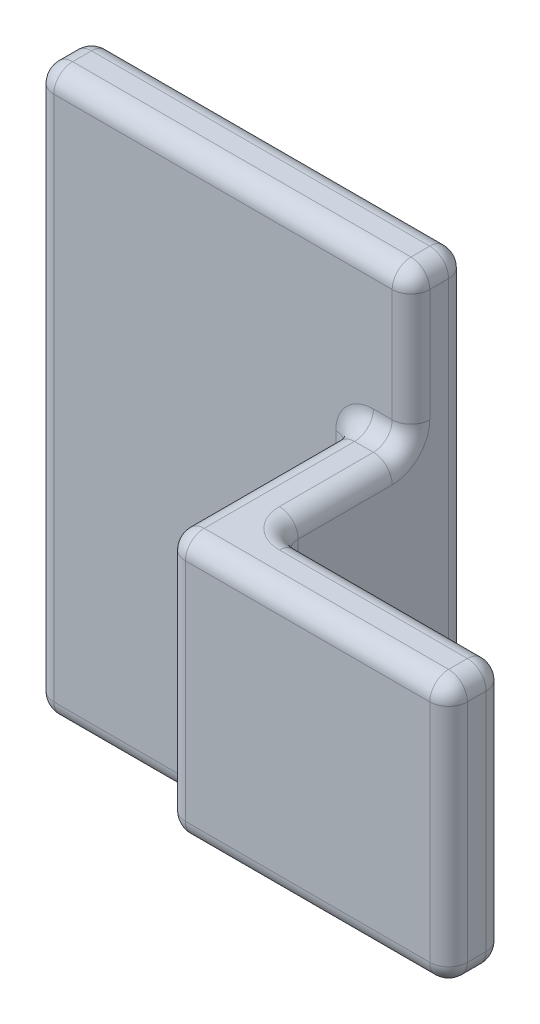
SolidWorks part; units mm, degrees
ref_plane "Front Plane" through (0, 0, 0) normal (0, 0, 1) x (1, 0, 0)
ref_plane "Top Plane" through (0, 0, 0) normal (0, 1, 0) x (1, 0, 0)
ref_plane "Right Plane" through (0, 0, 0) normal (1, 0, 0) x (0, 0, -1)
sketch "Sketch1" plane through (0, 0, 0) normal (0, 0, 1) x (1, 0, 0)
  line L0 (0, -30) -> (0, 0)
  line L3 (0, -30) -> (20, -30)
  line L4 (20, -30) -> (20, 0)
  line L5 (20, 0) -> (0, 0)
  line L6 (10, -7.5) -> (10, -22.5) construction
  line L7 (10, -15) -> (0, -15) construction
  line L8 (10, -15) -> (10, -30) construction
  circle A2 centre (10, -7.5) radius 2.25 construction
  circle A3 centre (10, -22.5) radius 2.25 construction
  dimension "D4" = 4.5
  dimension "D5" = 4.5
  dimension "D1" = 20
  dimension "D2" = 30
  dimension "D3" = 15
extrude "Boss-Extrude1" add sketch "Sketch1" along normal blind 3
ref_plane "Plane1" through (20, 0, 0) normal (-1, 0, 0) x (0, 0, 1)
sketch "Sketch3" plane through (20, 0, 0) normal (-1, 0, 0) x (0, 0, 1)
  line L0 (3, -8) -> (13, -8)
  line L1 (3, 0) -> (3, -30) construction
  line L2 (13, -8) -> (13, -22)
  line L3 (13, -22) -> (3, -22)
  line L4 (3, -22) -> (3, -8)
  dimension "D1" = 8
  dimension "D2" = 10
  dimension "D3" = 8
extrude "Boss-Extrude2" add sketch "Sketch3" along normal blind 3
sketch "Sketch4" plane through (17, 0, 0) normal (-1, 0, 0) x (0, 0, 1)
  line L0 (13, -8) -> (3, -8) construction
  line L1 (13, -22) -> (10, -22)
  line L2 (13, -22) -> (13, -8)
  line L3 (13, -8) -> (10, -8)
  line L4 (10, -22) -> (10, -8)
  dimension "D1" = 3
extrude "Boss-Extrude3" add sketch "Sketch4" against normal blind 15
ref_plane "Plane2" through (0, 0, 13) normal (0, 0, 1) x (1, 0, 0)
sketch "Sketch6" plane through (0, 0, 13) normal (0, 0, 1) x (1, 0, 0)
  line L1 (32, 14.1) -> (23, 14.1)
  line L2 (32, 14.1) -> (32, -44.1)
  line L3 (32, -44.1) -> (23, -44.1)
  line L4 (23, 14.1) -> (23, -44.1)
  dimension "D1" = 0
  dimension "D2" = 22.1
  dimension "D3" = 22.1
  dimension "D4" = 9
extrude "Boss-Extrude4" [suppressed] add sketch "Sketch6" against normal blind 2
sketch "Sketch7" [suppressed] plane through (0, 0, 21) normal (0, 0, -1) x (-1, 0, 0)
  line L2 (-38.6471, 43.1227) -> (-38.6471, 41.1227)
  line L5 (-38.6471, 43.1227) -> (-47.6471, 43.1227)
  line L6 (-47.6471, 43.1227) -> (-47.6471, 41.1227)
  line L7 (-47.6471, -35.8773) -> (-47.6471, 43.1227) construction
  line L8 (-47.6471, 41.1227) -> (-38.6471, 41.1227)
  dimension "D1" = 2
extrude "Boss-Extrude5" [suppressed] add sketch "Sketch7" along normal blind 18.4
sketch "Sketch9" [suppressed] plane through (0, 41.1227, 0) normal (0, -1, 0) x (1, 0, 0)
  line L2 (47.6471, 2.6) -> (47.6471, 4.6)
  line L5 (47.6471, 4.6) -> (41.6471, 4.6)
  line L6 (41.6471, 4.6) -> (41.6471, 2.6)
  line L7 (47.6471, 2.6) -> (38.6471, 2.6) construction
  line L8 (41.6471, 2.6) -> (47.6471, 2.6)
  dimension "D1" = 2
  dimension "D2" = 3
extrude "Boss-Extrude7" [suppressed] add sketch "Sketch9" along normal blind 3
mirror "Mirror2" [suppressed] about plane through (0, 0, 0) normal (0, 1, 0)
ref_plane "Plane3" [suppressed] through (38.6471, 0, 0) normal (-1, 0, 0) x (0, 0, 1)
sketch "Sketch10" [suppressed] plane through (38.6471, 0, 0) normal (-1, 0, 0) x (0, 0, 1)
  line L0 (23, -23.4) -> (15, -23.4)
  line L1 (23, -11) -> (23, 11) construction
  line L2 (15, -23.4) -> (15, -26.2)
  line L3 (15, -26.2) -> (23, -26.2)
  line L4 (23, -26.2) -> (23, -23.4)
  dimension "D1" = 8.5
  dimension "D2" = 5.7
  dimension "D3" = 8
sketch "Sketch11" plane through (20, 0, 0) normal (1, 0, 0) x (0, 0, -1)
  circle A0 centre (-19.6265, 5.2253) radius 1.25
  circle A1 centre (-19.6265, -4.7747) radius 1.175
  dimension "D1" = 2.5
  dimension "D2" = 2.35
  dimension "D3" = 10
extrude "Cut-Extrude1" [suppressed] cut sketch "Sketch11" against normal through all
fillet "Fillet1" radius 1 19 edges at (26, -8, 10) (26, -22, 10) (18.5, -8, 3) (18.5, -22, 3) (20, -8, 6.5) (20, -4, 3) (20, -26, 3) (20, -22, 6.5) (20, -15, 10) (32, -8, 11.5) (32, -15, 10) (32, -22, 11.5) (24.5, -8, 13) (32, -15, 13) (24.5, -22, 13) (17, -15, 3) (17, -8, 8) (17, -15, 13) (17, -22, 8)
fillet "Fillet2" radius 1 13 edges at (9.5, -30, 3) (10, -30, 0) (10, 0, 0) (9.5, 0, 3) (0, 0, 1.5) (0, -15, 3) (0, -30, 1.5) (0, -15, 0) (20, -30, 1) (20, 0, 1) (20, -15, 0) (19.7071, -30, 2.7071) (19.7071, 0, 2.7071)
